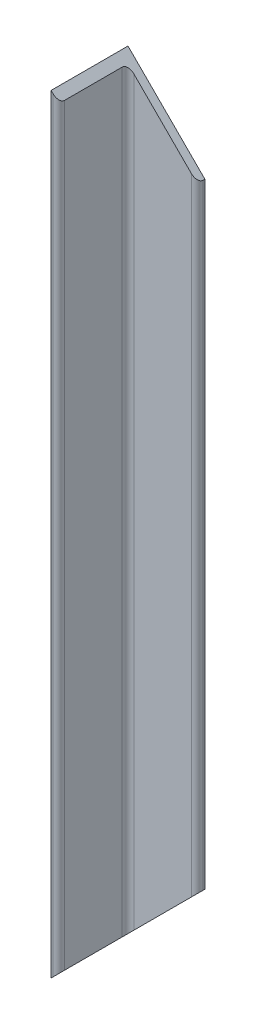
SolidWorks part; units mm, degrees
material "ASTM A36 Steel"
ref_plane "Front Plane" through (0, 0, 0) normal (0, 0, 1) x (1, 0, 0)
ref_plane "Top Plane" through (0, 0, 0) normal (0, 1, 0) x (1, 0, 0)
ref_plane "Right Plane" through (0, 0, 0) normal (1, 0, 0) x (0, 0, -1)
sketch "Sketch1" plane through (0, 0, 0) normal (0, 1, 0) x (1, 0, 0)
  line L0 (-27.4999, 29.2132) -> (-67.4999, 29.2132)
  line L1 (-67.4999, 29.2132) -> (-67.4999, -10.7868)
  line L2 (-67.4999, -10.7868) -> (-66.4999, -10.7868)
  line L3 (-63.4999, -7.7868) -> (-63.4999, 22.2132)
  line L4 (-60.4999, 25.2132) -> (-30.4999, 25.2132)
  line L5 (-27.4999, 28.2132) -> (-27.4999, 29.2132)
  arc A0 (-66.4999, -10.7868) -> (-63.4999, -7.7868) centre (-66.4999, -7.7868) ccw
  arc A1 (-63.4999, 22.2132) -> (-60.4999, 25.2132) centre (-60.4999, 22.2132) cw
  arc A2 (-30.4999, 25.2132) -> (-27.4999, 28.2132) centre (-30.4999, 28.2132) ccw
  point P8 (-63.4999, -10.7868)
  point P13 (-27.4999, 25.2132)
  dimension "D5" = 3
  dimension "D1" = 40
  dimension "D2" = 40
  dimension "D3" = 4
  dimension "D4" = 4
extrude "Boss-Extrude1" add sketch "Sketch1" along normal blind 400
sketch "Sketch2" plane through (0, 0, -29.2132) normal (0, 0, -1) x (-1, 0, 0)
  line L0 (67.4999, 0) -> (27.4999, 40)
  line L1 (27.4999, 400) -> (27.4999, 0) construction
  line L2 (27.4999, 40) -> (27.4999, 0)
  line L3 (27.4999, 0) -> (67.4999, 0)
  line L4 (27.4999, 400) -> (67.4999, 400) construction
  line L5 (27.4999, 400) -> (67.4999, 400)
  line L6 (27.4999, 360) -> (27.4999, 400)
  line L7 (67.4999, 400) -> (27.4999, 360)
  dimension "D1" = 40
  dimension "D2" = 0
extrude "Cut-Extrude1" cut sketch "Sketch2" against normal through all both and the other way through all
